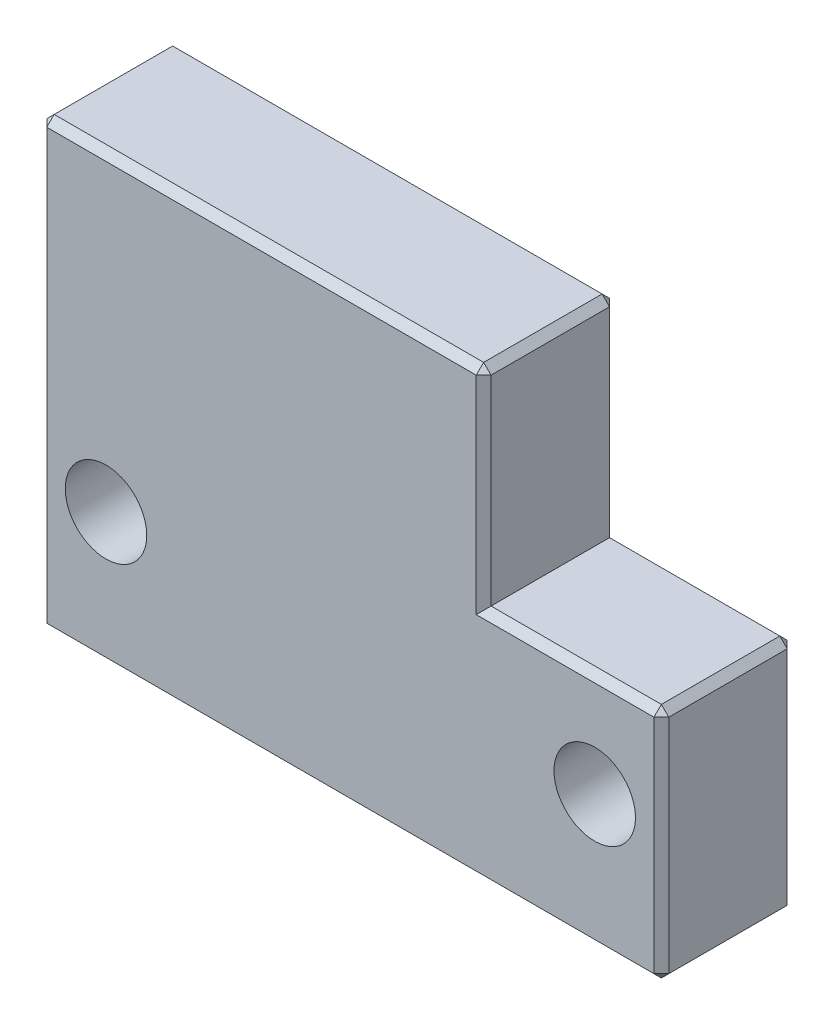
SolidWorks part; units mm, degrees
ref_plane "前视基准面" through (0, 0, 0) normal (0, 0, 1) x (1, 0, 0)
ref_plane "上视基准面" through (0, 0, 0) normal (0, 1, 0) x (1, 0, 0)
ref_plane "右视基准面" through (0, 0, 0) normal (1, 0, 0) x (0, 0, -1)
sketch "草图1" plane through (0, 0, 0) normal (0, 0, 1) x (1, 0, 0)
  line L1 (0, 0) -> (42, 0)
  line L2 (0, 0) -> (0, 30)
  line L3 (0, 30) -> (42, 30)
  line L4 (42, 0) -> (42, 30)
  dimension "D1" = 42
  dimension "D2" = 30
extrude "凸台-拉伸1" add sketch "草图1" along normal blind 9
sketch "草图2" plane through (0, 0, 0) normal (0, 0, -1) x (-1, 0, 0)
  line L1 (-42, 30) -> (-30, 30)
  line L2 (-42, 30) -> (-42, 16)
  line L3 (-42, 16) -> (-30, 16)
  line L4 (-30, 30) -> (-30, 16)
  dimension "D1" = 14
  dimension "D2" = 12
extrude "切除-拉伸1" cut sketch "草图2" against normal through all
chamfer "倒角1" distance 0.5 angle 45 17 edges at (0, 15, 0) (21, 0, 0) (36, 16, 0) (30, 23, 0) (21, 0, 9) (42, 0, 4.5) (42, 8, 9) (42, 8, 0) (42, 16, 4.5) (36, 16, 9) (30, 23, 9) (0, 30, 4.5) (15, 30, 0) (30, 30, 4.5) (15, 30, 9) (0, 15, 9) (0, 0, 4.5)
sketch "草图3" plane through (0, 0, 0) normal (0, 0, -1) x (-1, 0, 0)
  circle A0 centre (-37.5, 9) radius 2.75
  circle A1 centre (-4.5, 9) radius 2.75
extrude "切除-拉伸2" cut sketch "草图3" against normal through all
